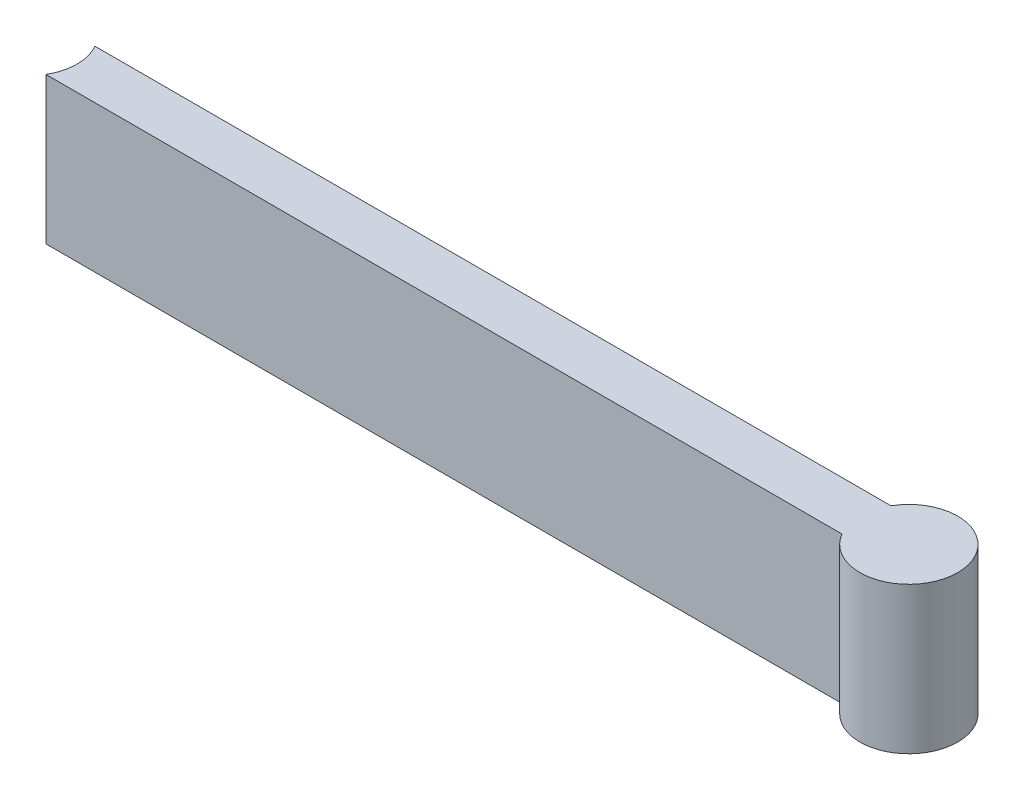
SolidWorks part; units mm, degrees
ref_plane "Front Plane" through (0, 0, 0) normal (0, 0, 1) x (1, 0, 0)
ref_plane "Top Plane" through (0, 0, 0) normal (0, 1, 0) x (1, 0, 0)
ref_plane "Right Plane" through (0, 0, 0) normal (1, 0, 0) x (0, 0, -1)
sketch "Sketch1" plane through (0, 0, 0) normal (0, 1, 0) x (1, 0, 0)
  line L0 (43.3013, -25) -> (856.6987, -25)
  line L1 (43.3013, 25) -> (856.6987, 25)
  line L2 (43.3013, -25) -> (43.3013, 25) construction
  arc A0 (43.3013, -25) -> (43.3013, 25) centre (0, 0) ccw
  arc A2 (856.6987, -25) -> (856.6987, 25) centre (900, 0) ccw
  arc A3 (-38.3022, -32.1394) -> (-46.9846, 17.101) centre (0, 0) ccw construction
  dimension "D1" = 50
  dimension "D2" = 900
extrude "Boss-Extrude1" add sketch "Sketch1" along normal up to surface (75 mm away) and the other way up to surface (75 mm away)
ref_point "Point1"
sketch3d "3DSketch1"
  line L0 (900, 0, 0) -> (900, 312.4781, 0)
  line L1 (900, 0, 0) -> (1059.8933, 0, 0) construction
